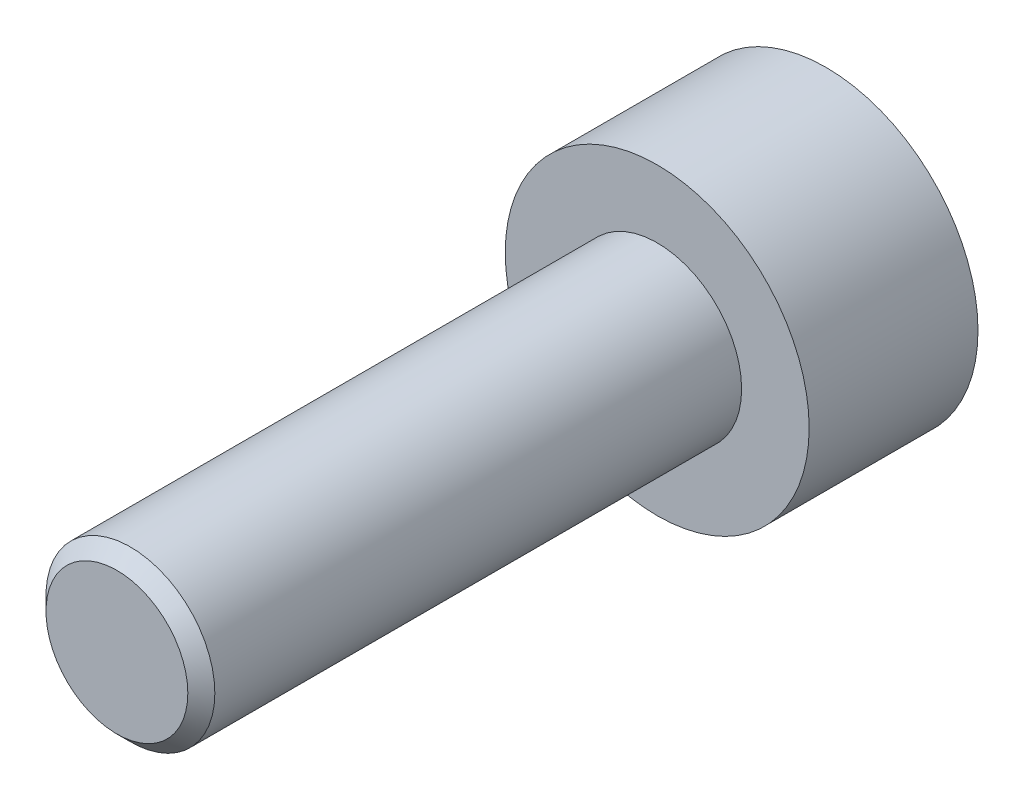
SolidWorks part; units mm, degrees
material "AISI 304"
ref_plane "前视基准面" through (0, 0, 0) normal (0, 0, 1) x (1, 0, 0)
ref_plane "上视基准面" through (0, 0, 0) normal (0, 1, 0) x (1, 0, 0)
ref_plane "右视基准面" through (0, 0, 0) normal (1, 0, 0) x (0, 0, -1)
sketch "草图1" plane through (0, 0, 0) normal (0, 0, 1) x (1, 0, 0)
  circle A0 centre (0, 0) radius 2.25
  dimension "D1" = 4.5
extrude "凸台-拉伸1" add sketch "草图1" along normal blind 2.5
sketch "草图2" plane through (0, 0, 2.5) normal (0, 0, 1) x (1, 0, 0)
  circle A0 centre (0, 0) radius 1.25
  dimension "D1" = 2.5
extrude "凸台-拉伸2" add sketch "草图2" along normal blind 8
chamfer "倒角1" distance 0.2 angle 45 1 edges at (1.25, 0, 10.5)
sketch "草图3" plane through (0, 0, 0) normal (0, 0, -1) x (-1, 0, 0)
  line L0 (0, 1.1778) -> (-1.02, 0.5889)
  line L1 (-1.02, 0.5889) -> (-1.02, -0.5889)
  line L2 (-1.02, -0.5889) -> (0, -1.1778)
  line L3 (0, -1.1778) -> (1.02, -0.5889)
  line L4 (1.02, -0.5889) -> (1.02, 0.5889)
  line L5 (1.02, 0.5889) -> (0, 1.1778)
  dimension "D1" = 2.04
extrude "切除-拉伸1" cut sketch "草图3" against normal blind 1.1
